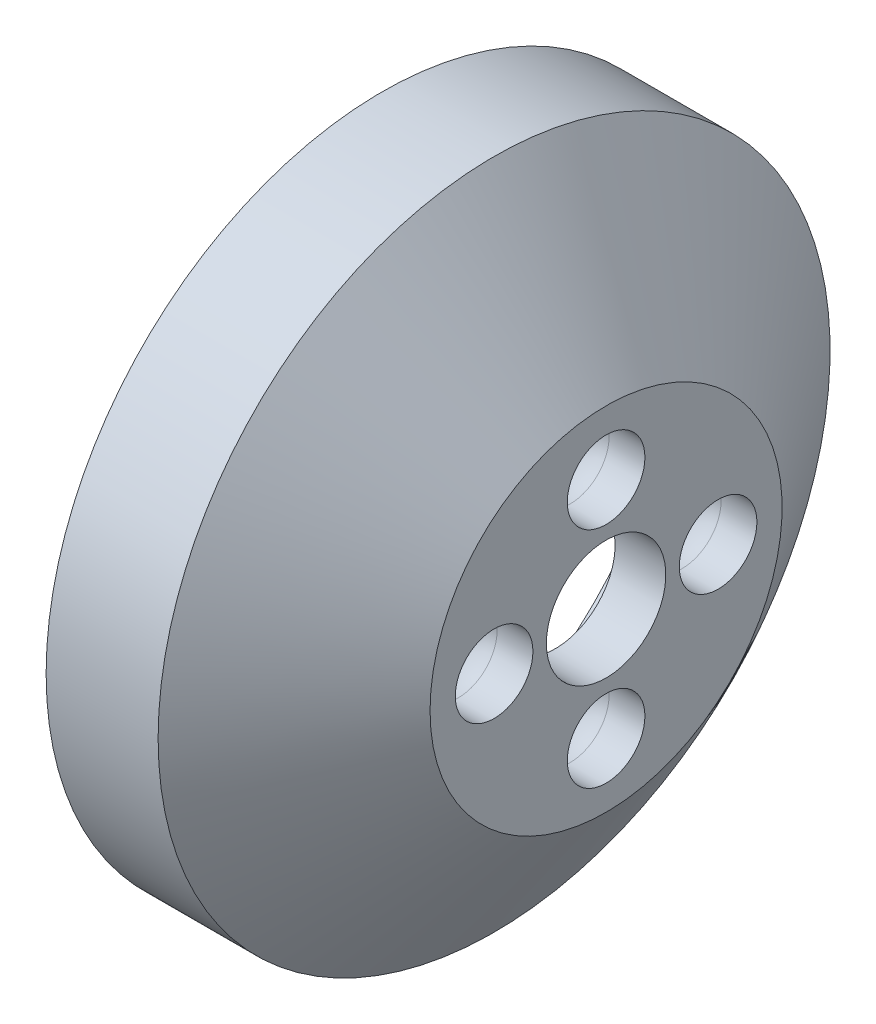
SolidWorks part; units mm, degrees
ref_plane "Front Plane" through (0, 0, 0) normal (0, 0, 1) x (1, 0, 0)
ref_plane "Top Plane" through (0, 0, 0) normal (0, 1, 0) x (1, 0, 0)
ref_plane "Right Plane" through (0, 0, 0) normal (1, 0, 0) x (0, 0, -1)
sketch "Sketch1" plane through (0, 0, 0) normal (0, 0, 1) x (1, 0, 0)
  line L2 (0, 0) -> (0, 57.15)
  line L3 (0, 57.15) -> (12.7, 57.15)
  line L5 (0, 57.15) -> (-6.35, 57.15)
  line L6 (0, 57.15) -> (0, 51.054)
  line L7 (0, 51.054) -> (-6.35, 51.054)
  line L8 (-6.35, 57.15) -> (-6.35, 51.054)
  line L9 (31.75, 0) -> (31.75, 29.9438)
  line L10 (31.75, 29.9438) -> (12.7, 57.15)
  line L11 (0, 0) -> (31.75, 0)
  line L12 (0, 10.16) -> (31.75, 10.16)
  dimension "D1" = 12.7
  dimension "D2" = 6.35
  dimension "D3" = 6.096
  dimension "D4" = 57.15
  dimension "D5" = 19.05
  dimension "D6" = 35
  dimension "D7" = 10.16
revolve "Revolve1" add sketch "Sketch1" angle 360 about L11
sketch "Sketch2" plane through (31.75, 0, 0) normal (1, 0, 0) x (0, 0, -1)
  line L0 (-29.9438, 0) -> (29.9438, 0) construction
  line L1 (0, 29.9438) -> (0, -29.9438) construction
  circle A0 centre (0, 0) radius 29.9438 construction
  circle A1 centre (-19.05, 0) radius 6.604
  circle A2 centre (0, 19.05) radius 6.604
  circle A3 centre (19.05, 0) radius 6.604
  circle A4 centre (0, -19.05) radius 6.604
  point P19 (0, 0)
  dimension "D2" = 13.208
  dimension "D1" = 19.05
  dimension "D3" = 4
extrude "Cut-Extrude1" cut sketch "Sketch2" against normal blind 12.7
fillet "Fillet1" radius 6.604 4 edges at (19.05, -19.05, -6.604) (19.05, 0, -25.654) (19.05, 0, 12.446) (19.05, 19.05, -6.604)
chamfer "Chamfer1" distance 33.02 angle 35 1 edges at (0, 0, 10.16)
